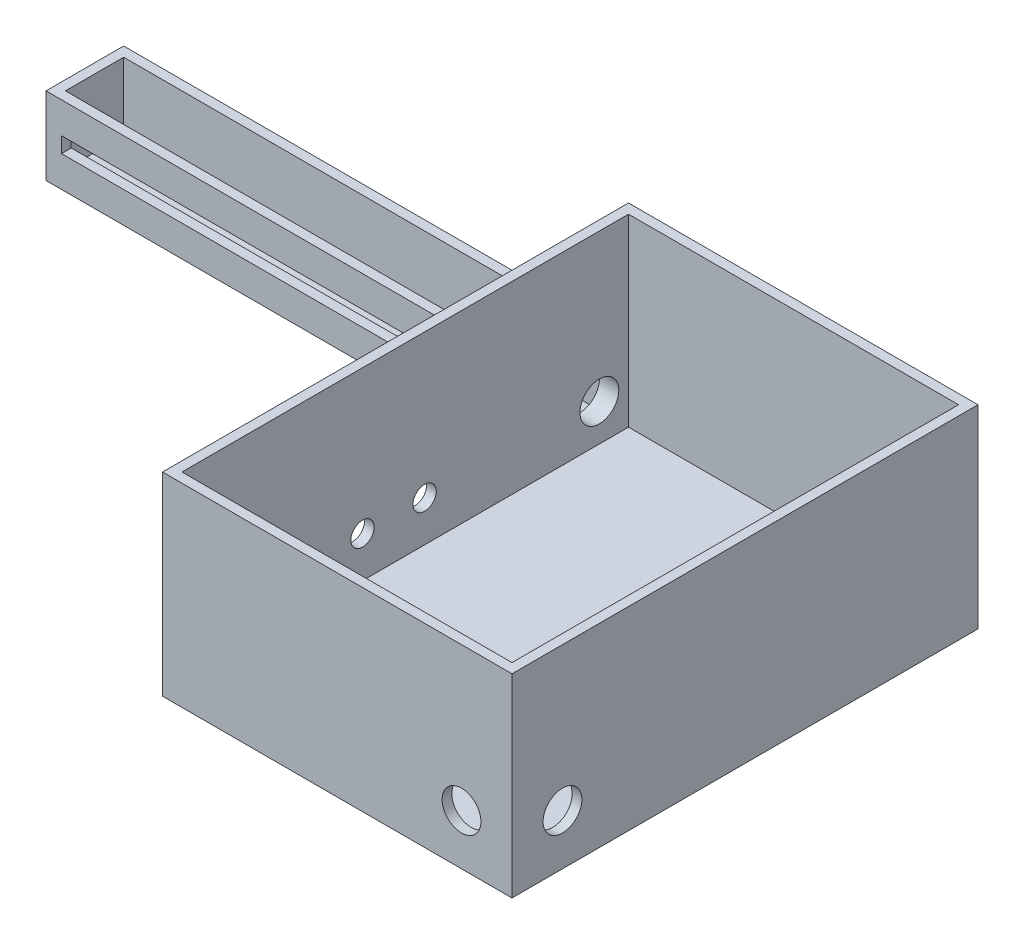
SolidWorks part; units mm, degrees
ref_plane "Front Plane" through (0, 0, 0) normal (0, 0, 1) x (1, 0, 0)
ref_plane "Top Plane" through (0, 0, 0) normal (0, 1, 0) x (1, 0, 0)
ref_plane "Right Plane" through (0, 0, 0) normal (1, 0, 0) x (0, 0, -1)
sketch "Sketch1" plane through (0, 0, 0) normal (0, 1, 0) x (1, 0, 0)
  line L1 (-82.55, 12.7) -> (82.55, 12.7)
  line L2 (-82.55, 12.7) -> (-82.55, -12.7)
  line L3 (-82.55, -12.7) -> (82.55, -12.7)
  line L5 (-82.55, 12.7) -> (82.55, -12.7) construction
  line L6 (-82.55, -12.7) -> (82.55, 12.7) construction
  line L7 (82.55, 12.7) -> (196.85, 12.7)
  line L8 (82.55, -12.7) -> (82.55, -139.7)
  line L9 (82.55, -139.7) -> (196.85, -139.7)
  line L10 (196.85, 12.7) -> (196.85, -139.7)
  point P0 (0, 0)
  dimension "D1" = 165.1
  dimension "D2" = 25.4
  dimension "D3" = 114.3
  dimension "D4" = 152.4
extrude "Boss-Extrude1" add sketch "Sketch1" along normal blind 63.5
sketch "Sketch2" plane through (0, 63.5, 0) normal (0, 1, 0) x (1, 0, 0)
  line L1 (-82.55, 12.7) -> (82.55, 12.7)
  line L2 (-82.55, 12.7) -> (-82.55, -12.7)
  line L3 (-82.55, -12.7) -> (82.55, -12.7)
  line L4 (82.55, 12.7) -> (82.55, -12.7)
extrude "Cut-Extrude1" cut sketch "Sketch2" against normal blind 38.1
sketch "Sketch3" plane through (0, 63.5, 0) normal (0, 1, 0) x (1, 0, 0)
  line L0 (82.55, -139.7) -> (196.85, -139.7) construction
  line L1 (85.725, 9.525) -> (193.675, 9.525)
  line L2 (85.725, 9.525) -> (85.725, -136.525)
  line L3 (85.725, -136.525) -> (193.675, -136.525)
  line L4 (193.675, 9.525) -> (193.675, -136.525)
  line L5 (196.85, -139.7) -> (196.85, 12.7) construction
  line L6 (82.55, 12.7) -> (82.55, -139.7) construction
  line L7 (196.85, 12.7) -> (82.55, 12.7) construction
  dimension "D1" = 3.175
  dimension "D2" = 3.175
  dimension "D3" = 3.175
  dimension "D4" = 3.175
extrude "Cut-Extrude2" cut sketch "Sketch3" against normal blind 60.325
sketch "Sketch4" plane through (0, 25.4, 0) normal (0, 1, 0) x (1, 0, 0)
  line L0 (82.55, 12.7) -> (-82.55, 12.7) construction
  line L1 (-79.375, 9.525) -> (79.375, 9.525)
  line L2 (-79.375, 9.525) -> (-79.375, -9.525)
  line L3 (-79.375, -9.525) -> (79.375, -9.525)
  line L4 (79.375, 9.525) -> (79.375, -9.525)
  line L5 (-82.55, 12.7) -> (-82.55, -12.7) construction
  line L6 (-82.55, -12.7) -> (82.55, -12.7) construction
  line L7 (82.55, -12.7) -> (82.55, 12.7) construction
  dimension "D1" = 3.175
  dimension "D2" = 3.175
  dimension "D3" = 3.175
  dimension "D4" = 3.175
extrude "Cut-Extrude3" cut sketch "Sketch4" against normal blind 22.225
sketch "Sketch5" plane through (79.375, 0, 0) normal (-1, 0, 0) x (0, 0, 1)
  line L0 (-12.7, 0) -> (12.7, 0) construction
  circle A0 centre (0, 15.24) radius 6.35
  dimension "D1" = 15.24
  dimension "D2" = 12.7
extrude "Cut-Extrude5" cut sketch "Sketch5" against normal blind 20.32 and the other way blind 20.32
sketch "Sketch6" plane through (0, 0, 12.7) normal (0, 0, 1) x (1, 0, 0)
  line L0 (-82.55, 25.4) -> (-82.55, 0) construction
  line L1 (-77.47, 15.24) -> (77.47, 15.24)
  line L2 (-77.47, 15.24) -> (-77.47, 10.16)
  line L3 (-77.47, 10.16) -> (77.47, 10.16)
  line L4 (77.47, 15.24) -> (77.47, 10.16)
  line L5 (-82.55, 25.4) -> (82.55, 25.4) construction
  line L6 (-82.55, 0) -> (82.55, 0) construction
  line L7 (82.55, 63.5) -> (82.55, 0) construction
  dimension "D1" = 5.08
  dimension "D2" = 10.16
  dimension "D3" = 10.16
  dimension "D4" = 5.08
  dimension "D5" = 5.08
extrude "Cut-Extrude6" cut sketch "Sketch6" against normal blind 10.16
sketch "Sketch8" plane through (82.55, 0, 0) normal (-1, 0, 0) x (0, 0, 1)
  line L0 (12.7, 0) -> (139.7, 0) construction
  line L1 (139.7, 63.5) -> (139.7, 0) construction
  circle A0 centre (57.15, 16.51) radius 3.81
  circle A1 centre (77.47, 16.51) radius 3.81
  circle A2 centre (97.79, 16.51) radius 3.81
  dimension "D1" = 3
  dimension "D2" = 16.51
  dimension "D3" = 41.91
extrude "Cut-Extrude8" cut sketch "Sketch8" against normal blind 12.7
sketch "Sketch9" plane through (0, 0, 139.7) normal (0, 0, 1) x (1, 0, 0)
  line L0 (82.55, 0) -> (196.85, 0) construction
  line L1 (196.85, 63.5) -> (196.85, 0) construction
  circle A0 centre (180.34, 16.51) radius 6.35
  dimension "D1" = 16.51
  dimension "D2" = 16.51
extrude "Cut-Extrude9" cut sketch "Sketch9" against normal blind 12.7
sketch "Sketch10" plane through (196.85, 0, 0) normal (1, 0, 0) x (0, 0, -1)
  line L0 (-139.7, 0) -> (12.7, 0) construction
  line L1 (-139.7, 63.5) -> (-139.7, 0) construction
  circle A0 centre (-123.19, 16.51) radius 6.35
  dimension "D1" = 16.51
  dimension "D2" = 16.51
extrude "Cut-Extrude10" cut sketch "Sketch10" against normal blind 12.7
